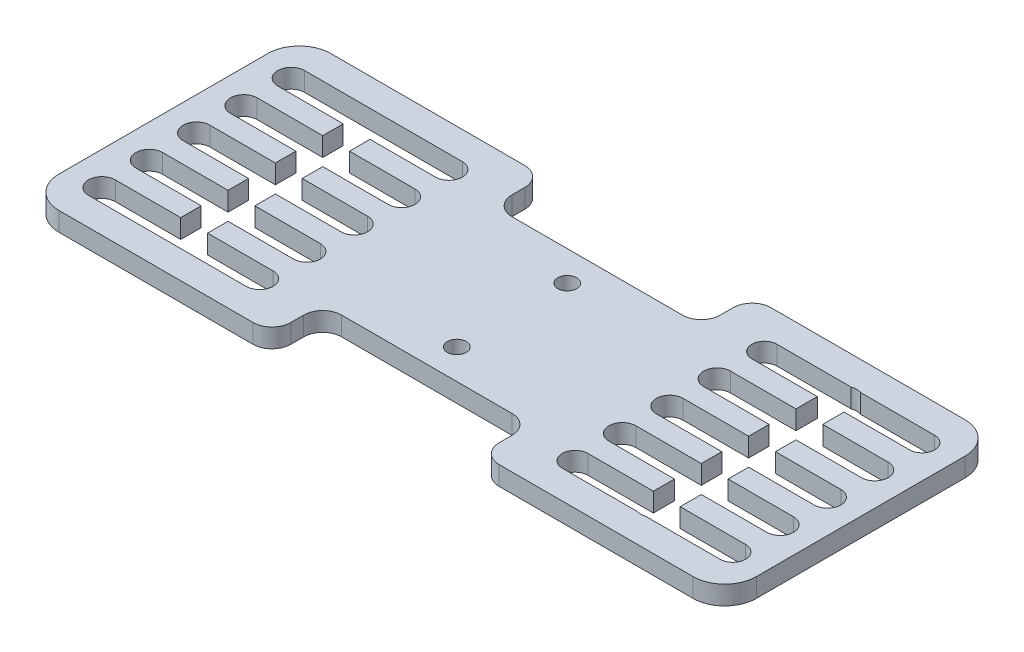
SolidWorks part; units mm, degrees
material "Fundición maleable"
ref_plane "Alzado" through (0, 0, 0) normal (0, 0, 1) x (1, 0, 0)
ref_plane "Planta" through (0, 0, 0) normal (0, 1, 0) x (1, 0, 0)
ref_plane "Vista lateral" through (0, 0, 0) normal (1, 0, 0) x (0, 0, -1)
sketch "Croquis1" plane through (0, 0, 0) normal (0, 1, 0) x (1, 0, 0)
  line L0 (-75, -30) -> (-75, 30) construction
  line L1 (75, -40) -> (-75, -40) construction
  line L2 (75, -40) -> (75, 40) construction
  line L3 (75, 40) -> (-75, 40) construction
  line L4 (-75, -40) -> (-75, 40) construction
  line L5 (75, -40) -> (-75, 40) construction
  line L6 (75, 40) -> (-75, -40) construction
  line L7 (-79.25, -30) -> (-79.25, 30)
  line L8 (-70.75, -30) -> (-70.75, 30)
  line L9 (-100, 30) -> (-50, 30) construction
  line L10 (-100, 34.25) -> (-50, 34.25)
  line L11 (-100, 25.75) -> (-50, 25.75)
  line L12 (-100, 15) -> (-50, 15) construction
  line L13 (-100, 19.25) -> (-50, 19.25)
  line L14 (-100, 10.75) -> (-50, 10.75)
  line L15 (-100, 0) -> (-50, 0) construction
  line L16 (-100, 4.25) -> (-50, 4.25)
  line L17 (-100, -4.25) -> (-50, -4.25)
  line L18 (-100, -15) -> (-50, -15) construction
  line L19 (-100, -10.75) -> (-50, -10.75)
  line L20 (-100, -19.25) -> (-50, -19.25)
  line L21 (-100, -30) -> (-50, -30) construction
  line L22 (-100, -25.75) -> (-50, -25.75)
  line L23 (-100, -34.25) -> (-50, -34.25)
  line L24 (0, 0) -> (0, -66.1277) construction
  line L25 (75, -30) -> (75, 30) construction
  line L26 (79.25, -30) -> (79.25, 30)
  line L27 (70.75, -30) -> (70.75, 30)
  line L28 (100, 0) -> (50, 0) construction
  line L29 (100, 4.25) -> (50, 4.25)
  line L30 (100, -4.25) -> (50, -4.25)
  line L31 (100, 15) -> (50, 15) construction
  line L32 (100, 19.25) -> (50, 19.25)
  line L33 (100, 10.75) -> (50, 10.75)
  line L34 (0, 0) -> (0, 62.3627) construction
  line L35 (100.5119, -43.0788) -> (39.0154, -43.0788)
  line L36 (100, -15) -> (50, -15) construction
  line L37 (100, -10.75) -> (50, -10.75)
  line L38 (100, -19.25) -> (50, -19.25)
  line L39 (110.5119, -33.0788) -> (110.5119, 33.0788)
  line L40 (100.5119, 43.0788) -> (39.0154, 43.0788)
  line L41 (-110.5119, -33.0788) -> (-110.5119, 33.0788)
  line L42 (110.5119, -43.0788) -> (-110.5119, 43.0788) construction
  line L43 (110.5119, 43.0788) -> (-110.5119, -43.0788) construction
  line L44 (50, 30) -> (100, 30) construction
  line L45 (-15.9354, 17.5) -> (15.9354, 17.5) construction
  line L46 (-15.9354, 17.5) -> (-15.9354, -17.5) construction
  line L47 (-15.9354, -17.5) -> (15.9354, -17.5) construction
  line L48 (15.9354, 17.5) -> (15.9354, -17.5) construction
  line L49 (-15.9354, 17.5) -> (15.9354, -17.5) construction
  line L50 (-15.9354, -17.5) -> (15.9354, 17.5) construction
  line L51 (50, 33.9878) -> (100, 33.9878)
  line L52 (50, 26.0122) -> (100, 26.0122)
  line L53 (50, -30) -> (100, -30) construction
  line L54 (50, -25.9432) -> (100, -25.9432)
  line L55 (50, -34.0568) -> (100, -34.0568)
  line L56 (-135.581, 0) -> (126.68, 0) construction
  line L57 (-39.0154, 43.0788) -> (-100.5119, 43.0788)
  line L58 (-33.0154, 37.0788) -> (-33.0154, 33)
  line L59 (-27.0154, 27) -> (27.0154, 27)
  line L60 (33.0154, 37.0788) -> (33.0154, 33)
  line L61 (-33.0154, 53.1576) -> (33.0154, 27) construction
  line L62 (-33.0154, 27) -> (33.0154, 53.1576) construction
  line L63 (33.0154, -37.0788) -> (33.0154, -33)
  line L64 (-27.0154, -27) -> (27.0154, -27)
  line L65 (-33.0154, -37.0788) -> (-33.0154, -33)
  line L67 (-39.0154, -43.0788) -> (-100.5119, -43.0788)
  arc A0 (-79.25, -30) -> (-70.75, -30) centre (-75, -30) ccw
  arc A1 (-70.75, 30) -> (-79.25, 30) centre (-75, 30) ccw
  arc A2 (-100, 34.25) -> (-100, 25.75) centre (-100, 30) ccw
  arc A3 (-50, 25.75) -> (-50, 34.25) centre (-50, 30) ccw
  arc A4 (-100, 19.25) -> (-100, 10.75) centre (-100, 15) ccw
  arc A5 (-50, 10.75) -> (-50, 19.25) centre (-50, 15) ccw
  arc A6 (-100, 4.25) -> (-100, -4.25) centre (-100, 0) ccw
  arc A7 (-50, -4.25) -> (-50, 4.25) centre (-50, 0) ccw
  arc A8 (-100, -10.75) -> (-100, -19.25) centre (-100, -15) ccw
  arc A9 (-50, -19.25) -> (-50, -10.75) centre (-50, -15) ccw
  arc A10 (-100, -25.75) -> (-100, -34.25) centre (-100, -30) ccw
  arc A11 (-50, -34.25) -> (-50, -25.75) centre (-50, -30) ccw
  arc A12 (79.25, -30) -> (70.75, -30) centre (75, -30) cw
  arc A13 (70.75, 30) -> (79.25, 30) centre (75, 30) cw
  arc A14 (100, 4.25) -> (100, -4.25) centre (100, 0) cw
  arc A15 (50, -4.25) -> (50, 4.25) centre (50, 0) cw
  arc A16 (100, 19.25) -> (100, 10.75) centre (100, 15) cw
  arc A17 (50, 10.75) -> (50, 19.25) centre (50, 15) cw
  arc A18 (100, -10.75) -> (100, -19.25) centre (100, -15) cw
  arc A19 (50, -19.25) -> (50, -10.75) centre (50, -15) cw
  circle A20 centre (0, 17.5) radius 3
  circle A21 centre (0, -17.5) radius 3
  arc A22 (50, 33.9878) -> (50, 26.0122) centre (50, 30) ccw
  arc A23 (100, 26.0122) -> (100, 33.9878) centre (100, 30) ccw
  arc A24 (50, -25.9432) -> (50, -34.0568) centre (50, -30) ccw
  arc A25 (100, -34.0568) -> (100, -25.9432) centre (100, -30) ccw
  arc A26 (110.5119, 33.0788) -> (100.5119, 43.0788) centre (100.5119, 33.0788) ccw
  arc A27 (100.5119, -43.0788) -> (110.5119, -33.0788) centre (100.5119, -33.0788) ccw
  arc A28 (-100.5119, -43.0788) -> (-110.5119, -33.0788) centre (-100.5119, -33.0788) cw
  arc A29 (-100.5119, 43.0788) -> (-110.5119, 33.0788) centre (-100.5119, 33.0788) ccw
  arc A30 (39.0154, -43.0788) -> (33.0154, -37.0788) centre (39.0154, -37.0788) cw
  arc A31 (33.0154, -33) -> (27.0154, -27) centre (27.0154, -33) ccw
  arc A32 (-33.0154, -37.0788) -> (-39.0154, -43.0788) centre (-39.0154, -37.0788) cw
  arc A33 (-27.0154, -27) -> (-33.0154, -33) centre (-27.0154, -33) ccw
  arc A34 (33.0154, 37.0788) -> (39.0154, 43.0788) centre (39.0154, 37.0788) cw
  arc A35 (27.0154, 27) -> (33.0154, 33) centre (27.0154, 33) ccw
  arc A36 (-33.0154, 33) -> (-27.0154, 27) centre (-27.0154, 33) ccw
  arc A37 (-33.0154, 37.0788) -> (-39.0154, 43.0788) centre (-39.0154, 37.0788) ccw
  point P0 (0, 0)
  point P8 (-75, 0)
  point P15 (-75, 30)
  point P23 (-75, 15)
  point P30 (-75, 0)
  point P37 (-75, -15)
  point P44 (-75, -30)
  point P52 (75, 0)
  point P65 (75, 15)
  point P76 (75, -15)
  point P92 (75, 30)
  point P98 (75, -30)
  point P116 (0, 40.0788)
  point P133 (33.0154, -27)
  point P136 (-33.0154, -43.0788)
  point P139 (-33.0154, -27)
  point P150 (-33.0154, 43.0788)
  dimension "D3" = 4.25
  dimension "D5" = 4.25
  dimension "D10" = 6
  dimension "D11" = 6
  dimension "D12" = 10
  dimension "D14" = 6
  dimension "D1" = 80
  dimension "D2" = 150
  dimension "D4" = 60
  dimension "D6" = 50
  dimension "D7" = 0
  dimension "D9" = 35
  dimension "D13" = 54
  dimension "D8" = 5
extrude "Saliente-Extruir1" add sketch "Croquis1" along normal blind 6 contours L58 A37 L57 A29 L41 A28 L67 A32 L65 A33 L64 A31 L63 A30 L35 A27 L39 A26 L40 A34 L60 A35 L59 A36 A11 L23 A10 L22 L7 L20 A8 L19 L17 A6 L16 L14 A4 L13 L11 A2 L10 A3 L8
equation "\"D5@Croquis1\"=\"D3@Croquis1\""
